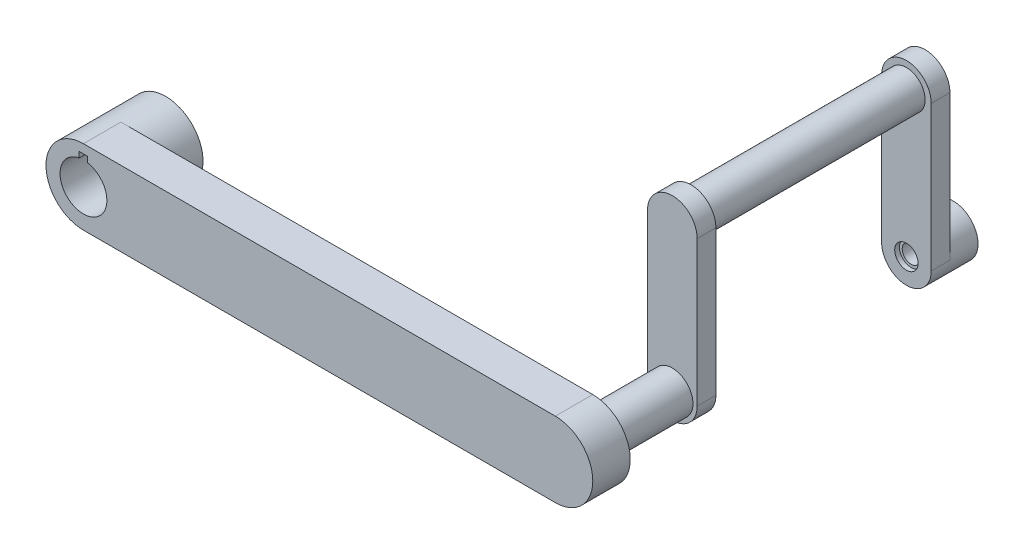
SolidWorks part; units mm, degrees
ref_plane "Alzado" through (0, 0, 0) normal (0, 0, 1) x (1, 0, 0)
ref_plane "Planta" through (0, 0, 0) normal (0, 1, 0) x (1, 0, 0)
ref_plane "Vista lateral" through (0, 0, 0) normal (1, 0, 0) x (0, 0, -1)
sketch "Croquis1" plane through (0, 0, 0) normal (0, 0, 1) x (1, 0, 0)
  line L0 (0, 0) -> (50.4, 0) construction
  line L1 (0, 4) -> (50.4, 4)
  line L2 (0, -4) -> (50.4, -4)
  line L3 (0, 0) -> (0, 2.5) construction
  line L6 (-0.45, 2.4592) -> (-0.45, 3.0592)
  line L7 (-0.45, 3.0592) -> (0.45, 3.0592)
  line L8 (0.45, 2.4592) -> (0.45, 3.0592)
  arc A0 (0, 4) -> (0, -4) centre (0, 0) ccw
  arc A1 (50.4, -4) -> (50.4, 4) centre (50.4, 0) ccw
  arc A2 (-0.45, 2.4592) -> (0.45, 2.4592) centre (0, 0) ccw
  dimension "D1" = 8
  dimension "D3" = 8
  dimension "D4" = 5
  dimension "D2" = 50.4
  dimension "D5" = 0.9
  dimension "D6" = 0.6
extrude "Saliente-Extruir1" add sketch "Croquis1" along normal blind 4
sketch "Croquis2" plane through (0, 0, 0) normal (0, 0, -1) x (-1, 0, 0)
  line L0 (-0.45, 2.4592) -> (-0.45, 3.0592)
  line L1 (-0.45, 3.0592) -> (0.45, 3.0592)
  line L2 (0.45, 3.0592) -> (0.45, 2.4592)
  arc A0 (-0.45, 2.4592) -> (0.45, 2.4592) centre (0, 0) ccw
  circle A1 centre (0, 0) radius 4
extrude "Saliente-Extruir2" add sketch "Croquis2" along normal blind 4.77
sketch "Croquis3" plane through (0, 0, 0) normal (0, 0, -1) x (-1, 0, 0)
  circle A0 centre (-50.4, 0) radius 2.2
  dimension "D1" = 4.4
extrude "Saliente-Extruir3" add sketch "Croquis3" along normal blind 8.5
sketch "Croquis4" plane through (0, 0, -8.5) normal (0, 0, -1) x (-1, 0, 0)
  line L0 (-50.4, 0) -> (-50.4, 15.5) construction
  line L1 (-53.05, 15.5) -> (-53.05, 0)
  line L2 (-47.75, 15.5) -> (-47.75, 0)
  arc A0 (-47.75, 15.5) -> (-53.05, 15.5) centre (-50.4, 15.5) ccw
  arc A1 (-53.05, 0) -> (-47.75, 0) centre (-50.4, 0) ccw
  dimension "D2" = 5.3
  dimension "D3" = 5.3
  dimension "D1" = 15.5
extrude "Saliente-Extruir4" add sketch "Croquis4" along normal blind 2
sketch "Croquis5" plane through (0, 0, -10.5) normal (0, 0, -1) x (-1, 0, 0)
  circle A0 centre (-50.4, 15.5) radius 2
  dimension "D1" = 4
extrude "Saliente-Extruir5" add sketch "Croquis5" along normal blind 23
sketch "Croquis6" plane through (0, 0, -33.5) normal (0, 0, -1) x (-1, 0, 0)
  line L0 (-53.05, 15.5) -> (-53.05, 0)
  line L1 (-47.75, 15.5) -> (-47.75, 0)
  arc A0 (-47.75, 15.5) -> (-53.05, 15.5) centre (-50.4, 15.5) ccw
  arc A1 (-53.05, 0) -> (-47.75, 0) centre (-50.4, 0) ccw
  circle A2 centre (-50.4, 0) radius 0.95
  dimension "D2" = 1.9
extrude "Saliente-Extruir6" add sketch "Croquis6" along normal blind 2
sketch "Croquis7" plane through (0, 0, -35.5) normal (0, 0, -1) x (-1, 0, 0)
  circle A1 centre (-50.4, 0) radius 2.65
  circle A2 centre (-50.4, 0) radius 0.95
extrude "Saliente-Extruir7" add sketch "Croquis7" along normal blind 3
sketch "Croquis8" plane through (0, 0, -33.5) normal (0, 0, 1) x (1, 0, 0)
  circle A0 centre (50.4, 0) radius 1.25
  dimension "D1" = 2.5
extrude "Cortar-Extruir1" cut sketch "Croquis8" against normal blind 0.5
